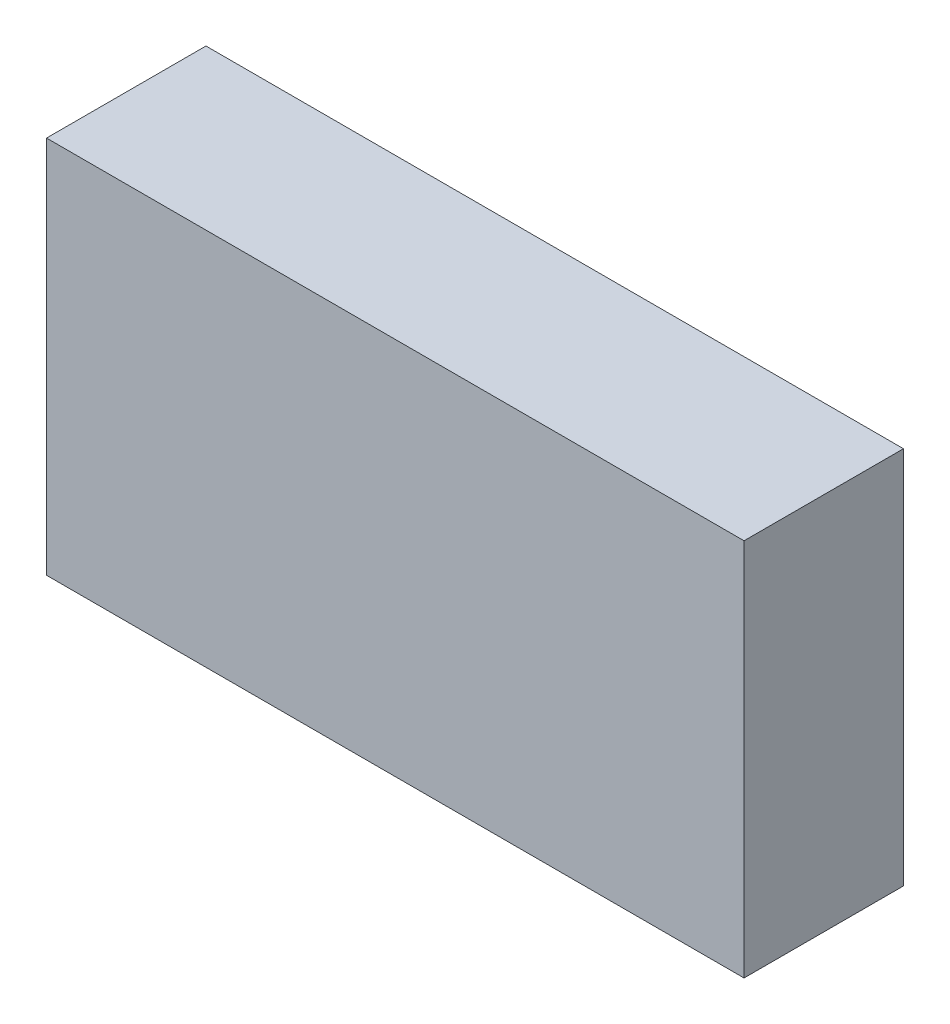
SolidWorks part; units mm, degrees
ref_plane "前视基准面" through (0, 0, 0) normal (0, 0, 1) x (1, 0, 0)
ref_plane "上视基准面" through (0, 0, 0) normal (0, 1, 0) x (1, 0, 0)
ref_plane "右视基准面" through (0, 0, 0) normal (1, 0, 0) x (0, 0, -1)
sketch "草图1" plane through (0, 0, 0) normal (0, 0, 1) x (1, 0, 0)
  line L0 (-0.875, -0.475) -> (0.875, -0.475)
  line L1 (0.875, -0.475) -> (0.875, 0.475)
  line L2 (0.875, 0.475) -> (-0.875, 0.475)
  line L3 (-0.875, 0.475) -> (-0.875, -0.475)
extrude "凸台-拉伸1" add sketch "草图1" along normal blind 0.4 from offset 0
